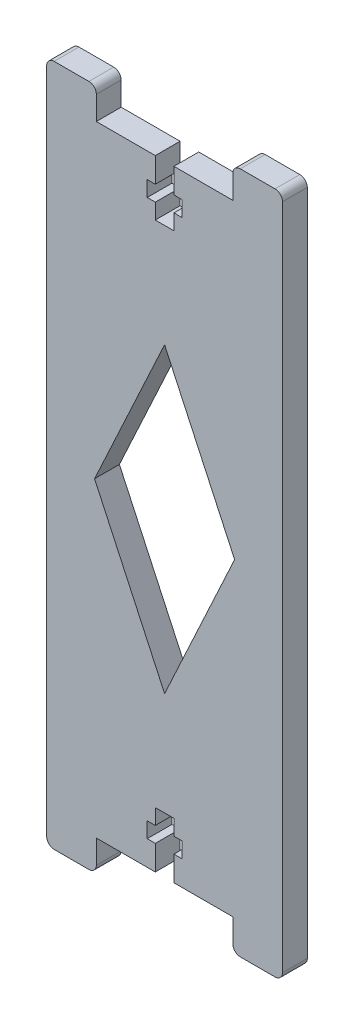
SolidWorks part; units mm, degrees
ref_plane "前视基准面" through (0, 0, 0) normal (0, 0, 1) x (1, 0, 0)
ref_plane "上视基准面" through (0, 0, 0) normal (0, 1, 0) x (1, 0, 0)
ref_plane "右视基准面" through (0, 0, 0) normal (1, 0, 0) x (0, 0, -1)
sketch "草图1" plane through (0, 0, 0) normal (0, 0, 1) x (1, 0, 0)
  line L0 (-4.0909, 0) -> (-4.0909, 7.8) construction
  line L1 (14.9091, 14) -> (14.9091, -96)
  line L2 (14.9091, -41) -> (-23.0909, -41) construction
  line L3 (-4.0909, -82) -> (-4.0909, -89.8) construction
  line L4 (6.9091, -96) -> (14.9091, -96)
  line L5 (6.9091, -91) -> (6.9091, -96)
  line L6 (-5.5909, 0) -> (-2.5909, 0)
  line L7 (-2.5909, 0) -> (-2.5909, 2.5)
  line L8 (-2.5909, 2.5) -> (-1.2909, 2.5)
  line L9 (-1.2909, 2.5) -> (-1.2909, 5)
  line L10 (-1.2909, 5) -> (-2.5909, 5)
  line L11 (-2.5909, 5) -> (-2.5909, 9)
  line L12 (-2.5909, 9) -> (6.9091, 9)
  line L13 (6.9091, 9) -> (6.9091, 14)
  line L14 (6.9091, 14) -> (14.9091, 14)
  line L15 (-2.5909, -91) -> (6.9091, -91)
  line L16 (-2.5909, -87) -> (-2.5909, -91)
  line L17 (-1.2909, -87) -> (-2.5909, -87)
  line L18 (-1.2909, -84.5) -> (-1.2909, -87)
  line L19 (-2.5909, -84.5) -> (-1.2909, -84.5)
  line L20 (-2.5909, -82) -> (-2.5909, -84.5)
  line L21 (-5.5909, -82) -> (-2.5909, -82)
  line L22 (-5.5909, -82) -> (-5.5909, -84.5)
  line L23 (-5.5909, -84.5) -> (-6.8909, -84.5)
  line L24 (-6.8909, -84.5) -> (-6.8909, -87)
  line L25 (-6.8909, -87) -> (-5.5909, -87)
  line L26 (-5.5909, -87) -> (-5.5909, -91)
  line L27 (-5.5909, -91) -> (-15.0909, -91)
  line L28 (-15.0909, 14) -> (-23.0909, 14)
  line L29 (-15.0909, 9) -> (-15.0909, 14)
  line L30 (-5.5909, 9) -> (-15.0909, 9)
  line L31 (-5.5909, 5) -> (-5.5909, 9)
  line L32 (-6.8909, 5) -> (-5.5909, 5)
  line L33 (-6.8909, 2.5) -> (-6.8909, 5)
  line L34 (-5.5909, 2.5) -> (-6.8909, 2.5)
  line L35 (-5.5909, 0) -> (-5.5909, 2.5)
  line L36 (-15.0909, -91) -> (-15.0909, -96)
  line L37 (-15.0909, -96) -> (-23.0909, -96)
  line L38 (-23.0909, 14) -> (-23.0909, -96)
  line L39 (-4.0909, 0) -> (-23.0909, -41) construction
  line L40 (-23.0909, -41) -> (-4.0909, -82) construction
  line L41 (-4.0909, -82) -> (14.9091, -41) construction
  line L42 (14.9091, -41) -> (-4.0909, 0) construction
  line L43 (-4.0909, -16.6484) -> (-15.3758, -41)
  line L44 (-15.3758, -41) -> (-4.0909, -65.3516)
  line L45 (-4.0909, -65.3516) -> (7.194, -41)
  line L46 (7.194, -41) -> (-4.0909, -16.6484)
  point P26 (-4.0909, -41)
  dimension "D1" = 1.5
  dimension "D2" = 2.5
  dimension "D3" = 2.8
  dimension "D4" = 2.5
  dimension "D5" = 4
  dimension "D6" = 9.5
  dimension "D7" = 5
  dimension "D8" = 8
  dimension "D9" = 110
  dimension "D10" = 7
extrude "凸台-拉伸1" add sketch "草图1" along normal blind 4
sketch "草图2" plane through (0, -91, 0) normal (0, -1, 0) x (1, 0, 0)
  line L0 (-5.5909, 2) -> (-2.5909, 2)
  line L1 (-5.5909, 4) -> (-5.5909, 0) construction
  line L2 (-2.5909, 4) -> (-2.5909, 0) construction
  circle A0 centre (-4.0909, 2) radius 1.5
fillet "圆角1" radius 1.2 8 edges at (-23.0909, 14, 2) (-15.0909, 14, 2) (6.9091, 14, 2) (14.9091, 14, 2) (-23.0909, -96, 2) (-15.0909, -96, 2) (6.9091, -96, 2) (14.9091, -96, 2)
